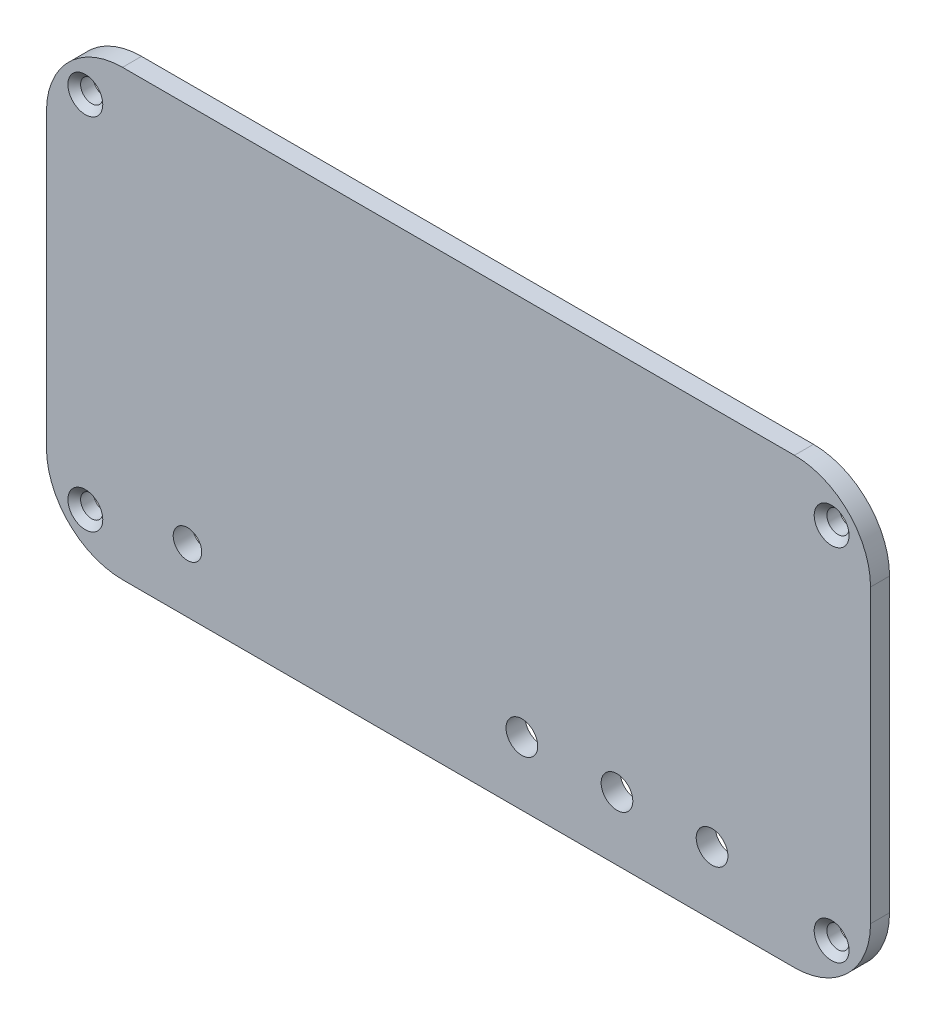
SolidWorks part; units mm, degrees
ref_plane "Спереди" through (0, 0, 0) normal (0, 0, 1) x (1, 0, 0)
ref_plane "Сверху" through (0, 0, 0) normal (0, 1, 0) x (1, 0, 0)
ref_plane "Справа" through (0, 0, 0) normal (1, 0, 0) x (0, 0, -1)
sketch "Эскиз2" plane through (0, 0, 0) normal (0, 0, 1) x (1, 0, 0)
  line L0 (0, -35) -> (0, -25) construction
  line L1 (-53, 35) -> (53, 35)
  line L2 (-65, 23) -> (-65, -23)
  line L3 (-53, -35) -> (53, -35)
  line L4 (65, 23) -> (65, -23)
  line L5 (-65, 35) -> (65, -35) construction
  line L6 (-65, -35) -> (65, 35) construction
  line L7 (0, -25) -> (10, -25) construction
  arc A0 (-65, -23) -> (-53, -35) centre (-53, -23) ccw
  arc A1 (53, -35) -> (65, -23) centre (53, -23) ccw
  arc A2 (53, 35) -> (65, 23) centre (53, 23) cw
  arc A3 (-53, 35) -> (-65, 23) centre (-53, 23) ccw
  circle A4 centre (10, -25) radius 2.5
  circle A5 centre (25, -25) radius 2.5
  circle A6 centre (40, -25) radius 2.5
  circle A7 centre (-42.7541, -25) radius 2.25
  point P0 (0, 0)
  dimension "D3" = 12
  dimension "D6" = 5
  dimension "D8" = 4.5
  dimension "D1" = 130
  dimension "D2" = 70
  dimension "D4" = 10
  dimension "D5" = 10
  dimension "D7" = 3
extrude "Бобышка-Вытянуть1" add sketch "Эскиз2" along normal blind 3
sketch "Эскиз3" plane through (0, 0, 0) normal (0, 0, -1) x (-1, 0, 0)
  line L0 (-10, -25) -> (0, -25) construction
  line L1 (-25, -25) -> (-25, -20) construction
  line L2 (-3, -21) -> (3, -21)
  line L3 (-3, -21) -> (-3, -29)
  line L4 (-3, -29) -> (3, -29)
  line L5 (3, -21) -> (3, -29)
  line L6 (-3, -21) -> (3, -29) construction
  line L7 (-3, -29) -> (3, -21) construction
  line L8 (-47, -29) -> (-53, -29)
  line L9 (-53, -21) -> (-53, -29)
  line L10 (-47, -21) -> (-53, -21)
  line L11 (-47, -21) -> (-47, -29)
  dimension "D1" = 10
  dimension "D2" = 6
  dimension "D3" = 8
extrude "Бобышка-Вытянуть2" add sketch "Эскиз3" along normal blind 3.4
sketch "Эскиз4" plane through (0, 0, -3.4) normal (0, 0, -1) x (-1, 0, 0)
  line L0 (-53, -25) -> (-47, -25) construction
  line L1 (-53, -21) -> (-53, -29) construction
  line L2 (-47, -29) -> (-47, -21) construction
  line L3 (-47, -25) -> (-50, -21) construction
  line L4 (-47, -21) -> (-53, -21) construction
  line L5 (-50, -21) -> (-50, -25) construction
  line L6 (-25, -25) -> (-25, -20) construction
  circle A0 centre (-50, -25) radius 1.25
  circle A1 centre (0, -25) radius 1.25
  dimension "D1" = 2.5
extrude "Вырез-Вытянуть1" cut sketch "Эскиз4" against normal blind 5
sketch "Эскиз5" plane through (0, 0, 3) normal (0, 0, 1) x (1, 0, 0)
  circle A0 centre (-58.8652, 28.3549) radius 1.75
  circle A1 centre (-58.8652, -28.3549) radius 1.75
  circle A2 centre (58.8652, 28.3549) radius 1.75
  circle A3 centre (58.8652, -28.3549) radius 1.75
  dimension "D1" = 3.5
  dimension "D2" = 3.5
  dimension "D3" = 3.5
  dimension "D4" = 3.5
extrude "Вырез-Вытянуть2" cut sketch "Эскиз5" against normal blind 3 and the other way through all
chamfer "Фаска1" distance 1 angle 45 4 edges at (60.6152, -28.3549, 3) (60.6152, 28.3549, 3) (-57.1152, -28.3549, 3) (-57.1152, 28.3549, 3)
